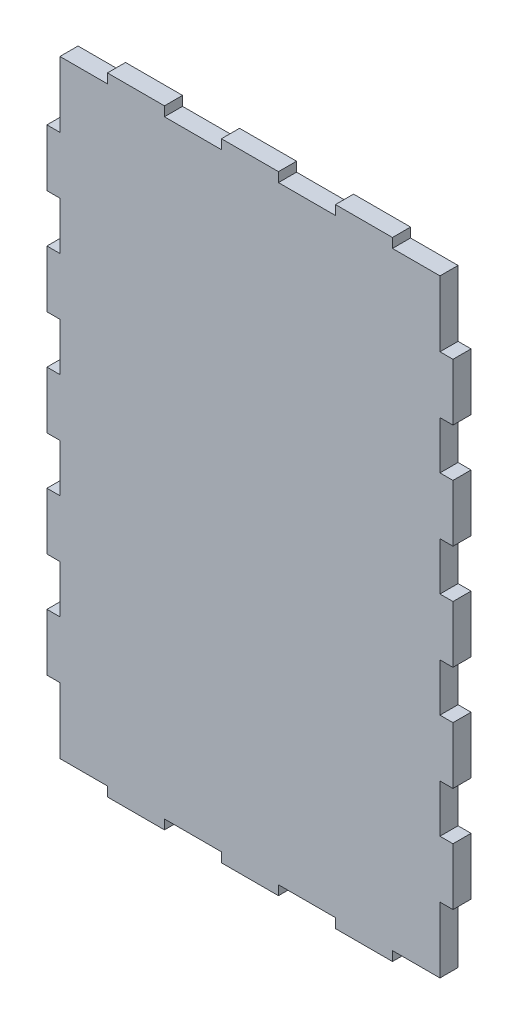
SolidWorks part; units mm, degrees
ref_plane "Front Plane" through (0, 0, 0) normal (0, 0, 1) x (1, 0, 0)
ref_plane "Top Plane" through (0, 0, 0) normal (0, 1, 0) x (1, 0, 0)
ref_plane "Right Plane" through (0, 0, 0) normal (1, 0, 0) x (0, 0, -1)
sketch "Sketch1" plane through (0, 0, 0) normal (0, 0, 1) x (1, 0, 0)
  line L1 (-63.5, -101.6) -> (63.5, -101.6)
  line L2 (-63.5, -101.6) -> (-63.5, 101.6)
  line L3 (-63.5, 101.6) -> (63.5, 101.6)
  line L4 (63.5, -101.6) -> (63.5, 101.6)
  line L5 (-63.5, -101.6) -> (63.5, 101.6) construction
  line L6 (-63.5, 101.6) -> (63.5, -101.6) construction
  point P0 (0, 0)
  dimension "D1" = 203.2
  dimension "D2" = 127
extrude "Boss-Extrude1" add sketch "Sketch1" along normal blind 6.0452
sketch "Sketch2" plane through (0, 0, 6.0452) normal (0, 0, 1) x (1, 0, 0)
  line L0 (63.5, 101.6) -> (-63.5, 101.6) construction
  line L1 (-9.525, 98.425) -> (9.525, 98.425)
  line L2 (-9.525, 98.425) -> (-9.525, 104.775)
  line L3 (-9.525, 104.775) -> (9.525, 104.775)
  line L4 (9.525, 98.425) -> (9.525, 104.775)
  line L5 (-9.525, 98.425) -> (9.525, 104.775) construction
  line L6 (-9.525, 104.775) -> (9.525, 98.425) construction
  line L7 (-47.625, 104.775) -> (-28.575, 104.775)
  line L8 (-28.575, 98.425) -> (-28.575, 104.775)
  line L9 (-47.625, 98.425) -> (-28.575, 98.425)
  line L10 (-47.625, 98.425) -> (-47.625, 104.775)
  line L11 (0, 101.6) -> (0, 0) construction
  line L12 (47.625, 98.425) -> (47.625, 104.775)
  line L13 (47.625, 98.425) -> (28.575, 98.425)
  line L14 (28.575, 98.425) -> (28.575, 104.775)
  line L15 (47.625, 104.775) -> (28.575, 104.775)
  line L16 (0, 0) -> (63.5, 0) construction
  line L17 (63.5, -101.6) -> (63.5, 101.6) construction
  line L18 (-9.525, -104.775) -> (9.525, -98.425) construction
  line L19 (-9.525, -98.425) -> (9.525, -104.775) construction
  line L20 (47.625, -104.775) -> (28.575, -104.775)
  line L21 (28.575, -98.425) -> (28.575, -104.775)
  line L22 (47.625, -98.425) -> (28.575, -98.425)
  line L23 (47.625, -98.425) -> (47.625, -104.775)
  line L24 (-47.625, -98.425) -> (-47.625, -104.775)
  line L25 (-47.625, -98.425) -> (-28.575, -98.425)
  line L26 (-28.575, -98.425) -> (-28.575, -104.775)
  line L27 (-47.625, -104.775) -> (-28.575, -104.775)
  line L28 (9.525, -98.425) -> (9.525, -104.775)
  line L29 (-9.525, -104.775) -> (9.525, -104.775)
  line L30 (-9.525, -98.425) -> (-9.525, -104.775)
  line L31 (-9.525, -98.425) -> (9.525, -98.425)
  point P0 (0, 101.6)
  point P33 (0, -101.6)
  dimension "D1" = 19.05
  dimension "D2" = 6.35
  dimension "D3" = 2
extrude "Boss-Extrude2" add sketch "Sketch2" against normal up to surface (6.0452 mm away) up to face at (0, 0, 0)
sketch "Sketch3" plane through (0, 0, 6.0452) normal (0, 0, 1) x (1, 0, 0)
  line L0 (63.5, -101.6) -> (63.5, 101.6) construction
  line L1 (59.1566, -9.525) -> (67.8434, -9.525)
  line L2 (59.1566, -9.525) -> (59.1566, 9.525)
  line L3 (59.1566, 9.525) -> (67.8434, 9.525)
  line L4 (67.8434, -9.525) -> (67.8434, 9.525)
  line L5 (59.1566, -9.525) -> (67.8434, 9.525) construction
  line L6 (59.1566, 9.525) -> (67.8434, -9.525) construction
  line L7 (59.1566, 25.527) -> (67.8434, 25.527)
  line L8 (67.8434, 25.527) -> (67.8434, 44.577)
  line L9 (59.1566, 44.577) -> (67.8434, 44.577)
  line L10 (59.1566, 25.527) -> (59.1566, 44.577)
  line L11 (59.1566, 60.579) -> (67.8434, 60.579)
  line L12 (67.8434, 60.579) -> (67.8434, 79.629)
  line L13 (59.1566, 79.629) -> (67.8434, 79.629)
  line L14 (59.1566, 60.579) -> (59.1566, 79.629)
  line L15 (0, 0) -> (-63.5, 0) construction
  line L16 (-63.5, 101.6) -> (-63.5, -101.6) construction
  line L17 (59.1566, -60.579) -> (59.1566, -79.629)
  line L18 (59.1566, -79.629) -> (67.8434, -79.629)
  line L19 (67.8434, -60.579) -> (67.8434, -79.629)
  line L20 (59.1566, -60.579) -> (67.8434, -60.579)
  line L21 (59.1566, -25.527) -> (59.1566, -44.577)
  line L22 (59.1566, -44.577) -> (67.8434, -44.577)
  line L23 (67.8434, -25.527) -> (67.8434, -44.577)
  line L24 (59.1566, -25.527) -> (67.8434, -25.527)
  line L25 (0, 104.775) -> (0, 0) construction
  line L26 (9.525, 104.775) -> (-9.525, 104.775) construction
  line L27 (-59.1566, 9.525) -> (-67.8434, -9.525) construction
  line L28 (-59.1566, -9.525) -> (-67.8434, 9.525) construction
  line L29 (-59.1566, -25.527) -> (-67.8434, -25.527)
  line L30 (-67.8434, -25.527) -> (-67.8434, -44.577)
  line L31 (-59.1566, -44.577) -> (-67.8434, -44.577)
  line L32 (-59.1566, -25.527) -> (-59.1566, -44.577)
  line L33 (-59.1566, -60.579) -> (-67.8434, -60.579)
  line L34 (-67.8434, -60.579) -> (-67.8434, -79.629)
  line L35 (-59.1566, -79.629) -> (-67.8434, -79.629)
  line L36 (-59.1566, -60.579) -> (-59.1566, -79.629)
  line L37 (-59.1566, 60.579) -> (-59.1566, 79.629)
  line L38 (-59.1566, 79.629) -> (-67.8434, 79.629)
  line L39 (-67.8434, 60.579) -> (-67.8434, 79.629)
  line L40 (-59.1566, 60.579) -> (-67.8434, 60.579)
  line L41 (-59.1566, 25.527) -> (-59.1566, 44.577)
  line L42 (-59.1566, 44.577) -> (-67.8434, 44.577)
  line L43 (-67.8434, 25.527) -> (-67.8434, 44.577)
  line L44 (-59.1566, 25.527) -> (-67.8434, 25.527)
  line L45 (-67.8434, -9.525) -> (-67.8434, 9.525)
  line L46 (-59.1566, 9.525) -> (-67.8434, 9.525)
  line L47 (-59.1566, -9.525) -> (-59.1566, 9.525)
  line L48 (-59.1566, -9.525) -> (-67.8434, -9.525)
  point P0 (63.5, 0)
  dimension "D1" = 19.05
  dimension "D2" = 8.6868
  dimension "D3" = 3
extrude "Boss-Extrude3" add sketch "Sketch3" against normal up to surface (6.0452 mm away) up to face at (0, 0, 0)
